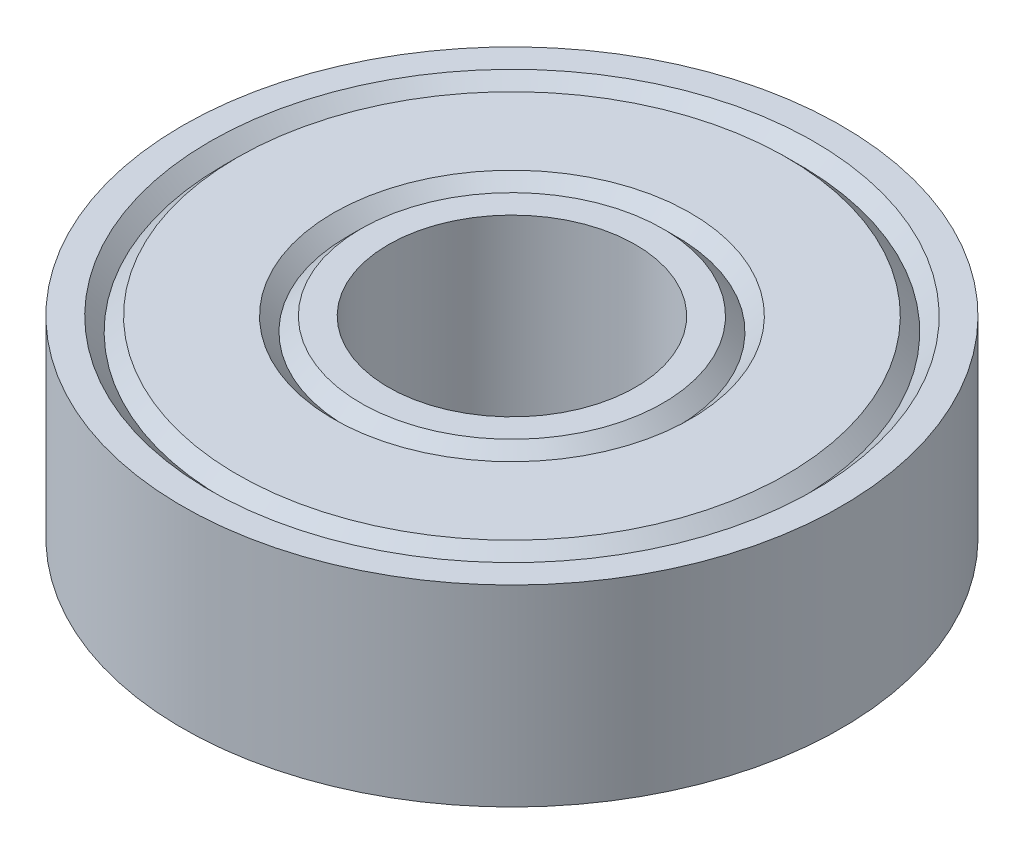
SolidWorks part; units mm, degrees
ref_plane "Front Plane" through (0, 0, 0) normal (0, 0, 1) x (1, 0, 0)
ref_plane "Top Plane" through (0, 0, 0) normal (0, 1, 0) x (1, 0, 0)
ref_plane "Right Plane" through (0, 0, 0) normal (1, 0, 0) x (0, 0, -1)
sketch "Sketch1" plane through (0, 0, 0) normal (0, 0, 1) x (1, 0, 0)
  line L0 (0, 3.5) -> (0, -3.5) construction
  line L1 (-4.5, 3.5) -> (-5.5, 3.5)
  line L2 (-4.5, 3.5) -> (-4.5, -3.5)
  line L3 (-4.5, -3.5) -> (-5.5, -3.5)
  line L4 (-12, 3.5) -> (-12, -3.5)
  line L5 (-11, 3.5) -> (-10.5, 3)
  line L6 (-10.5, 3) -> (-10, 3.5)
  line L7 (-6.5, 3.5) -> (-6, 3)
  line L8 (-6, 3) -> (-5.5, 3.5)
  line L9 (-11, -3.5) -> (-10.5, -3)
  line L10 (-10.5, -3) -> (-10, -3.5)
  line L11 (-6.5, -3.5) -> (-6, -3)
  line L12 (-6, -3) -> (-5.5, -3.5)
  line L13 (-6.5, -3.5) -> (-10, -3.5)
  line L14 (-11, -3.5) -> (-12, -3.5)
  line L15 (-11, 3.5) -> (-12, 3.5)
  line L16 (-6.5, 3.5) -> (-10, 3.5)
  line L17 (-10.5, 3) -> (-6, 3) construction
  line L18 (-10.5, 3) -> (-10.5, -3) construction
  line L19 (-6, -3) -> (-10.5, -3) construction
  line L20 (-6, 3) -> (-6, -3) construction
  line L21 (-10.5, 0) -> (-9, 0) construction
  line L22 (-5.5, 3.5) -> (-6.5, 3.5) construction
  line L23 (-9, 0) -> (-7.5, 0) construction
  line L24 (-10.5, 0) -> (-12, 0) construction
  line L25 (-7.5, 0) -> (-6, 0) construction
  line L26 (-6, 0) -> (-4.5, 0) construction
  dimension "D1" = 7
  dimension "D2" = 9
  dimension "D3" = 24
revolve "Revolve1" add sketch "Sketch1" angle 360 about L0
